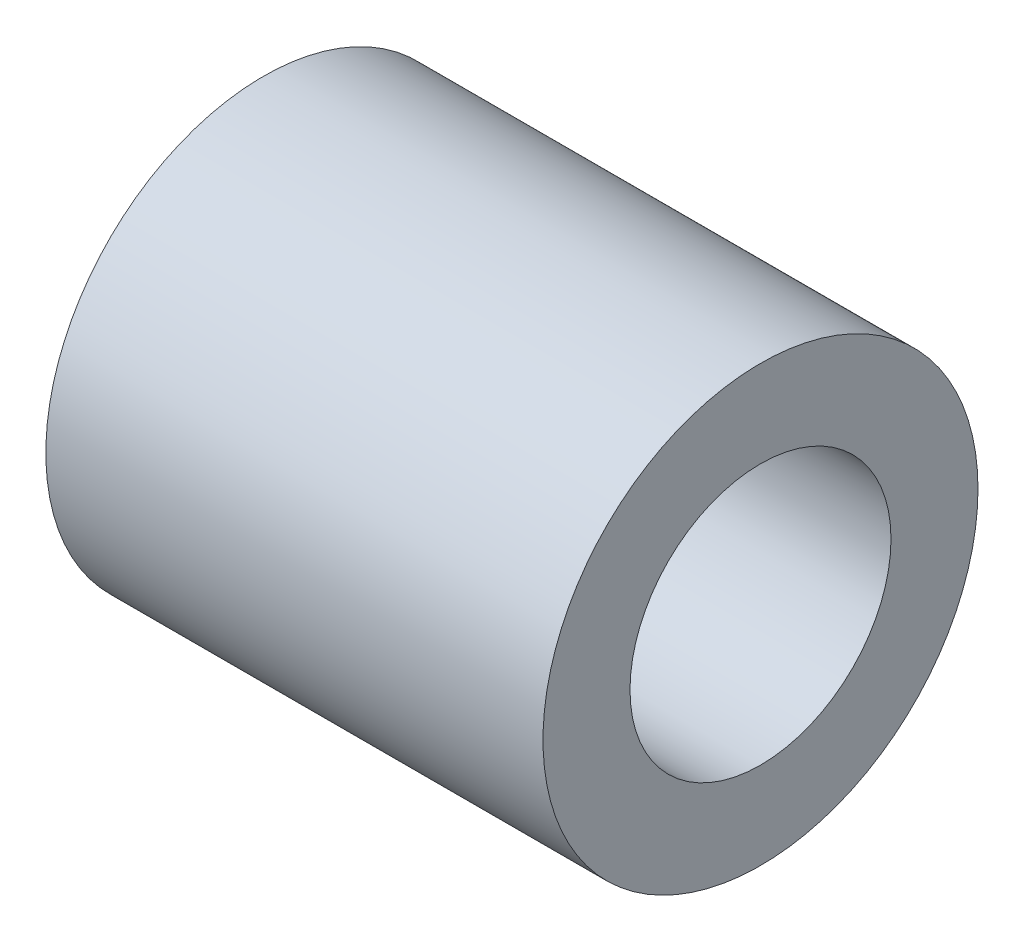
SolidWorks part; units mm, degrees
material "ABS"
ref_plane "Front" through (0, 0, 0) normal (0, 0, 1) x (1, 0, 0)
ref_plane "Top" through (0, 0, 0) normal (0, 1, 0) x (1, 0, 0)
ref_plane "Right" through (0, 0, 0) normal (1, 0, 0) x (0, 0, -1)
sketch "草图1" plane through (0, 0, 0) normal (1, 0, 0) x (0, -1, 0)
  circle A0 centre (0, 0) radius 3.5
  circle A1 centre (0, 0) radius 2.1
  dimension "垫圈内径" = 4.2
  dimension "垫圈外径" = 7
extrude "凸台-拉伸1" add sketch "草图1" along normal mid plane 8
